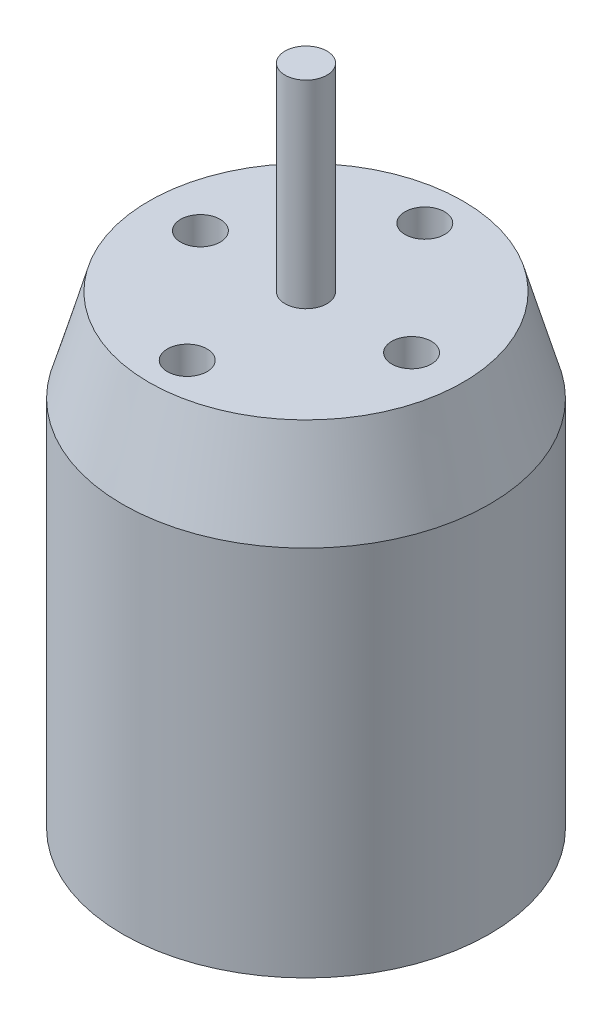
SolidWorks part; units mm, degrees
ref_plane "Front Plane" through (0, 0, 0) normal (0, 0, 1) x (1, 0, 0)
ref_plane "Top Plane" through (0, 0, 0) normal (0, 1, 0) x (1, 0, 0)
ref_plane "Right Plane" through (0, 0, 0) normal (1, 0, 0) x (0, 0, -1)
sketch "Sketch1" plane through (0, 0, 0) normal (0, 1, 0) x (1, 0, 0)
  circle A0 centre (0, 0) radius 13.9
  dimension "D1" = 27.8
extrude "Boss-Extrude1" add sketch "Sketch1" along normal blind 35.2
sketch "Sketch2" plane through (0, 35.2, 0) normal (0, 1, 0) x (1, 0, 0)
  circle A0 centre (0, 0) radius 1.585
  dimension "D1" = 3.17
extrude "Boss-Extrude2" add sketch "Sketch2" along normal blind 15
sketch "Sketch4" plane through (0, 35.2, 0) normal (0, 1, 0) x (1, 0, 0)
  circle A0 centre (0, 0) radius 9 construction
  circle A1 centre (0, 0) radius 8 construction
  circle A2 centre (0, 9) radius 1.5
  circle A3 centre (-8, 0) radius 1.5
  circle A4 centre (8, 0) radius 1.5
  circle A5 centre (0, -9) radius 1.5
  point P4 (-8, 0)
  point P5 (8, 0)
  point P6 (0, 9)
  point P7 (0, -9)
  dimension "D1" = 18
  dimension "D2" = 16
extrude "Cut-Extrude1" cut sketch "Sketch4" against normal blind 7
chamfer "Chamfer1" distance 7 distance2 2 1 edges at (0, 35.2, 13.9)
sketch "Sketch5" plane through (0, 0, 0) normal (0, -1, 0) x (1, 0, 0)
  circle A0 centre (0, 0) radius 4.5
  dimension "D1" = 9
extrude "Boss-Extrude3" add sketch "Sketch5" along normal blind 5
